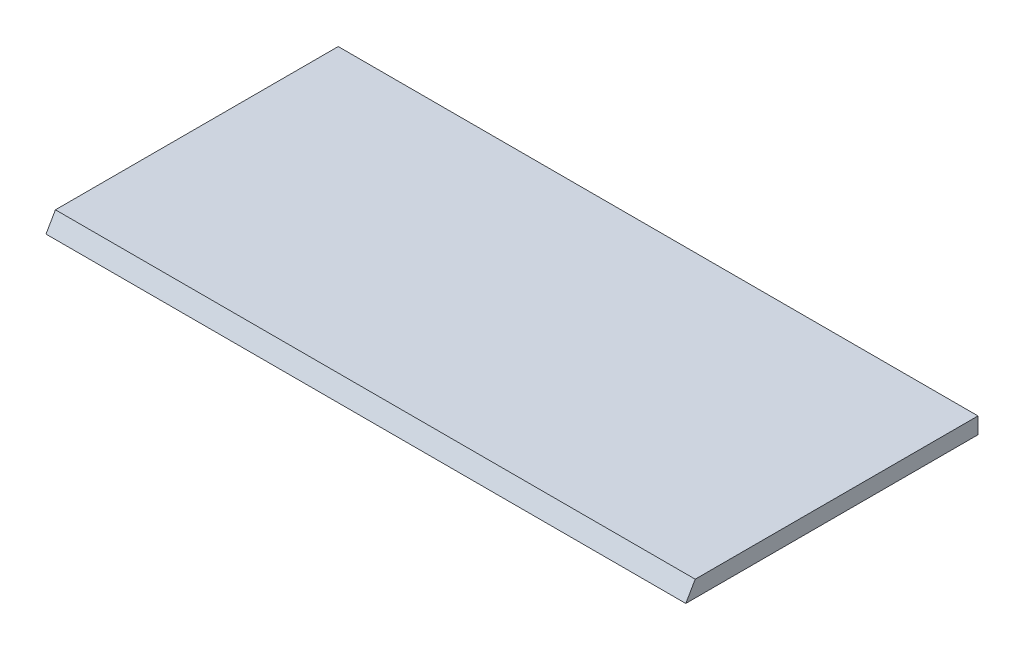
SolidWorks part; units mm, degrees
ref_plane "Alzado" through (0, 0, 0) normal (0, 0, 1) x (1, 0, 0)
ref_plane "Planta" through (0, 0, 0) normal (0, 1, 0) x (1, 0, 0)
ref_plane "Vista lateral" through (0, 0, 0) normal (1, 0, 0) x (0, 0, -1)
sketch "Croquis1" plane through (0, 0, 0) normal (1, 0, 0) x (0, 0, -1)
  line L0 (0, 0) -> (89.52, 0)
  line L1 (89.52, 0) -> (89.52, 5)
  line L2 (89.52, 5) -> (2.8868, 5)
  line L3 (0, 0) -> (2.8868, 5)
  point P3 (0, 0)
  dimension "D1" = 89.52
  dimension "D2" = 5
  dimension "D3" = 120
extrude "Saliente-Extruir1" add sketch "Croquis1" along normal blind 196
shell "Vaciado1" thickness 4
